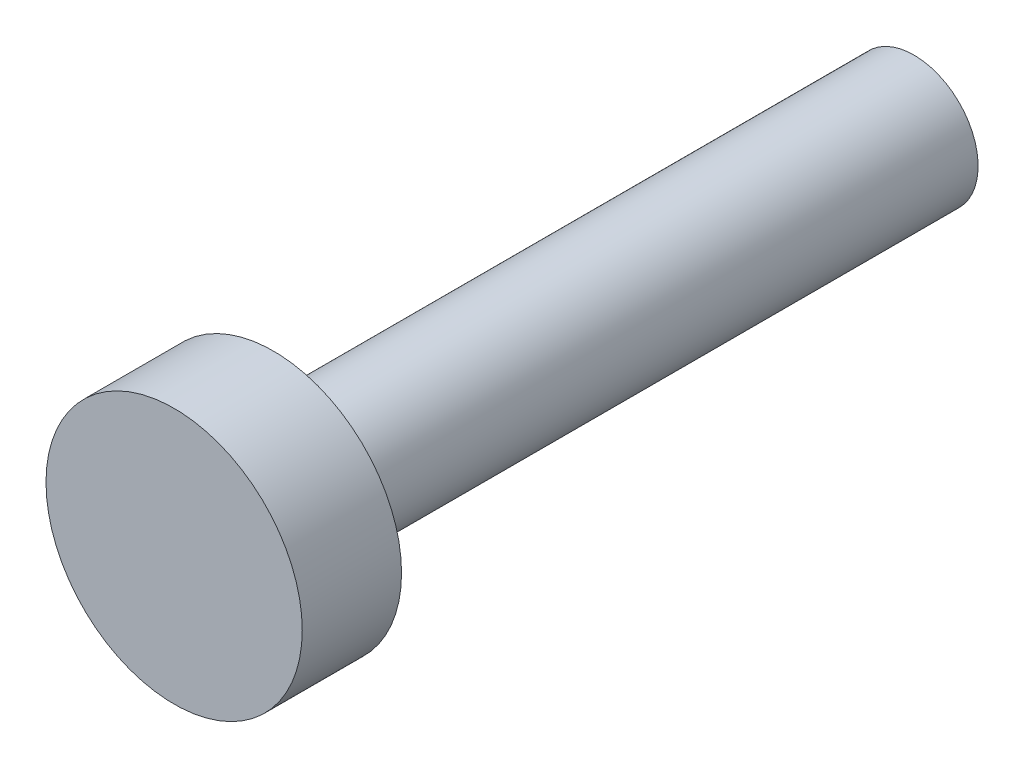
SolidWorks part; units mm, degrees
ref_plane "Plan de face" through (0, 0, 0) normal (0, 0, 1) x (1, 0, 0)
ref_plane "Plan de dessus" through (0, 0, 0) normal (0, 1, 0) x (1, 0, 0)
ref_plane "Plan de droite" through (0, 0, 0) normal (1, 0, 0) x (0, 0, -1)
sketch "Esquisse1" plane through (0, 0, 0) normal (0, 0, 1) x (1, 0, 0)
  circle A0 centre (0, 0) radius 4
  dimension "D1" = 8
extrude "Boss.-Extru.1" add sketch "Esquisse1" along normal blind 3.1
sketch "Esquisse2" plane through (0, 0, 0) normal (0, 0, -1) x (-1, 0, 0)
  circle A0 centre (0, 0) radius 2
  dimension "D1" = 4
extrude "Boss.-Extru.2" add sketch "Esquisse2" along normal blind 20
